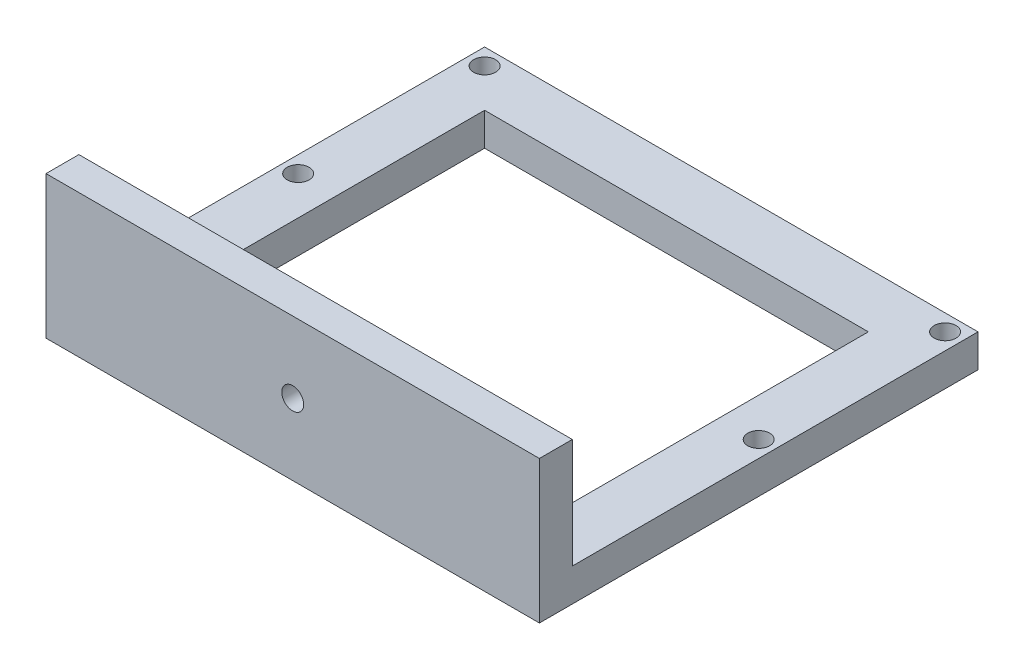
SolidWorks part; units mm, degrees
material "1060 Alloy"
ref_plane "Front Plane" through (0, 0, 0) normal (0, 0, 1) x (1, 0, 0)
ref_plane "Top Plane" through (0, 0, 0) normal (0, 1, 0) x (1, 0, 0)
ref_plane "Right Plane" through (0, 0, 0) normal (1, 0, 0) x (0, 0, -1)
sketch "Sketch2" plane through (0, 0, 0) normal (0, 1, 0) x (1, 0, 0)
  line L1 (0, 0) -> (-5, 0)
  line L2 (0, 0) -> (0, 40)
  line L3 (0, 40) -> (-5, 40)
  line L4 (-5, 0) -> (-5, 40)
  line L5 (-40, 0) -> (-45, 0)
  line L10 (-40, 0) -> (-40, 40)
  line L11 (-40, 40) -> (-45, 40)
  line L12 (-45, 0) -> (-45, 40)
  line L17 (-40, 40) -> (-5, 40)
  line L19 (-40, 35) -> (-5, 35)
  line L21 (-40, 0) -> (-5, 0)
  line L23 (-40, 5) -> (-5, 5)
  dimension "D1" = 40
  dimension "D2" = 5
  dimension "D3" = 40
  dimension "D4" = 5
  dimension "D5" = 45
  dimension "D6" = 5
  dimension "D7" = 5
extrude "Boss-Extrude1" add sketch "Sketch2" along normal blind 3 contours L12 L5 L10 L11 | L10 L19 L4 L17 | L4 L1 L2 L3 | L23 L10 L21 L4
hole_wizard "Ø2.0mm Dowel Hole1" positions "3DSketch1" profile "Sketch3" hole size "Ø2.0" standard "ANSI Metric"
sketch3d "3DSketch1"
  line L0 (-45, 0, 0) -> (-45, 0, -40) construction
  line L1 (0, 0, 0) -> (0, 0, -40) construction
  line L2 (0, 0, -40) -> (-45, 0, -40) construction
  point P0 (-1.5, 0, -38.5)
  point P2 (-43.5, 0, -38.5)
  point P11 (-1.5, 0, -21.5)
  point P13 (-43.5, 0, -21.5)
  point P16 (0, 0, 0)
  dimension "D1" = 1.5
  dimension "D2" = 1.5
  dimension "D3" = 1.5
  dimension "D4" = 1.5
  dimension "D5" = 17
  dimension "D6" = 1.5
  dimension "D7" = 1.5
sketch "Sketch3" plane through (-1.5, 0, -38.5) normal (1, 0, 0) x (0, 0, -1)
  line L0 (0, 0) -> (0, 12.6299)
  line L1 (0, 12.6299) -> (1, 12.029)
  line L2 (1, 12.029) -> (1, 0)
  line L5 (1, 0) -> (0, 0)
  line L10 (0, 12.6299) -> (-1, 12.029) construction
  line L11 (0, -6.35) -> (0, 107.95) construction
  dimension "Hole Dia." = 2
  dimension "Hole Depth" = 12.029
  dimension "Drill Angle" = 118
sketch "Sketch4" plane through (0, 3, 0) normal (0, 1, 0) x (1, 0, 0)
  line L4 (-45, 0) -> (-45, 40) construction
  line L5 (0, 0) -> (-45, 0)
  line L6 (0, 0) -> (0, 3)
  line L7 (0, 3) -> (-45, 3)
  line L8 (-45, 0) -> (-45, 3)
  dimension "D1" = 3
extrude "Boss-Extrude2" add sketch "Sketch4" along normal blind 10
sketch "Sketch5" plane through (0, 0, -3) normal (0, 0, -1) x (-1, 0, 0)
  line L4 (22.5, 13) -> (22.5, 0) construction
  line L5 (0, 13) -> (45, 13) construction
  line L6 (0, 0) -> (45, 0) construction
  point P17 (22.5, 6.5)
hole_wizard "Ø2.0mm Dowel Hole2" positions "Sketch5" profile "Sketch6" hole size "Ø2.0" standard "ANSI Metric"
sketch "Sketch6" plane through (-22.5, 6.5, -3) normal (1, 0, 0) x (0, 1, 0)
  line L0 (0, 0) -> (0, 12.6009)
  line L1 (0, 12.6009) -> (1, 12)
  line L2 (1, 12) -> (1, 0)
  line L5 (1, 0) -> (0, 0)
  line L10 (0, 12.6009) -> (-1, 12) construction
  line L11 (0, -6.35) -> (0, 107.95) construction
  dimension "Hole Dia." = 2
  dimension "Hole Depth" = 12
  dimension "Drill Angle" = 118
